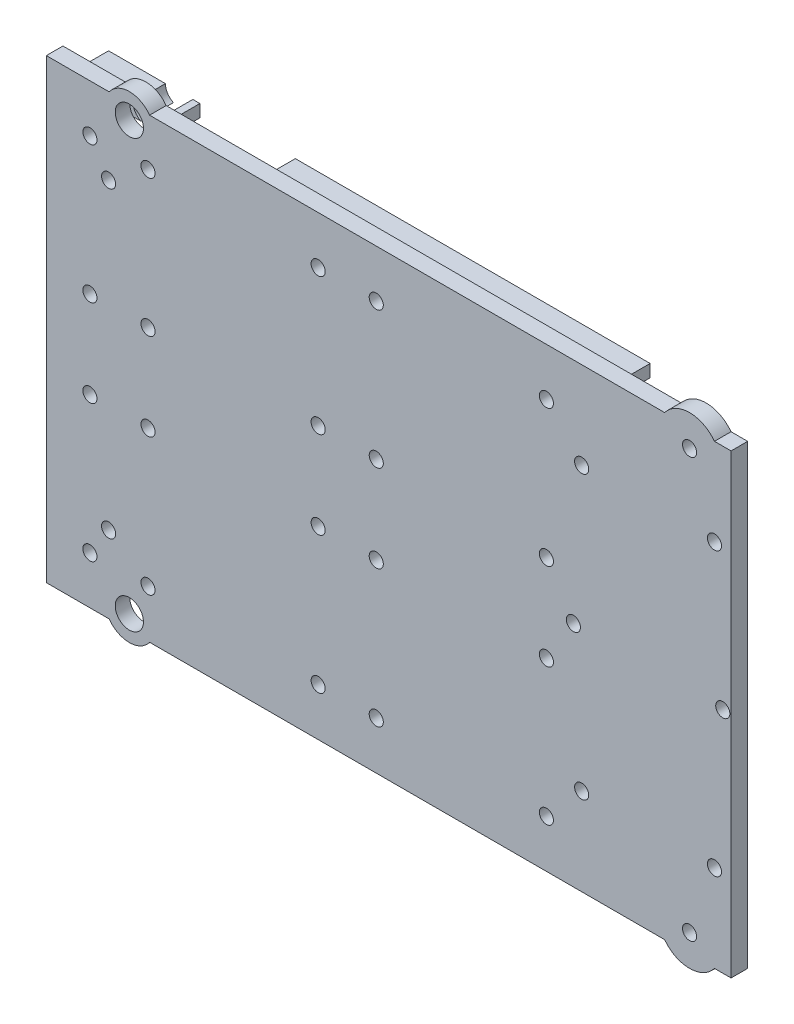
SolidWorks part; units mm, degrees
other "Platform Segment 3"
ref_plane "Front Plane" through (0, 0, 0) normal (0, 0, 1) x (1, 0, 0)
ref_plane "Top Plane" through (0, 0, 0) normal (0, 1, 0) x (1, 0, 0)
ref_plane "Right Plane" through (0, 0, 0) normal (1, 0, 0) x (0, 0, -1)
sketch3d "Main Profile Sketch datum points"
  point P0 (0, 0, 48.5)
  point P1 (10, 0, 48.5)
  point P2 (0, 10, 48.5)
ref_plane "Main Profile Sketch plane" through (0, 0, 48.5) normal (0, 0, 1) x (1, 0, 0)
sketch "Main Profile Sketch" plane through (0, 0, 48.5) normal (0, 0, 1) x (1, 0, 0)
  line L0 (55, -55) -> (70.1266, -55)
  line L1 (55, 55) -> (55, -55)
  line L2 (55, 55) -> (70.1266, 55)
  line L3 (79.8734, 55) -> (204, 55)
  line L4 (216, 55) -> (220, 55)
  line L5 (220, 55) -> (220, -55)
  line L6 (216, -55) -> (220, -55)
  line L7 (79.8734, -55) -> (204, -55)
  arc A0 (70.1266, -55) -> (79.8734, -55) centre (75, -51.5) ccw
  arc A1 (79.8734, 55) -> (70.1266, 55) centre (75, 51.5) ccw
  arc A2 (216, 55) -> (204, 55) centre (210, 50.5) ccw
  arc A3 (204, -55) -> (216, -55) centre (210, -50.5) ccw
  circle A4 centre (75, -51.5) radius 3.4
  circle A5 centre (65.5, -43.5) radius 1.7
  circle A6 centre (70, -36.5) radius 1.7
  circle A7 centre (79.5, -43.5) radius 1.7
  circle A8 centre (120.5, -43.5) radius 1.7
  circle A9 centre (134.5, -43.5) radius 1.7
  circle A10 centre (65.5, -10.5) radius 1.7
  circle A11 centre (79.5, -10.5) radius 1.7
  circle A12 centre (120.5, -10.5) radius 1.7
  circle A13 centre (134.5, -10.5) radius 1.7
  circle A14 centre (175.5, -43.5) radius 1.7
  circle A15 centre (210, -50.5) radius 1.7
  circle A16 centre (184, -34) radius 1.7
  circle A17 centre (216, -34) radius 1.7
  circle A18 centre (175.5, -10.5) radius 1.7
  circle A19 centre (65.5, 10.5) radius 1.7
  circle A20 centre (79.5, 10.5) radius 1.7
  circle A21 centre (120.5, 10.5) radius 1.7
  circle A22 centre (134.5, 10.5) radius 1.7
  circle A23 centre (70, 36.5) radius 1.7
  circle A24 centre (65.5, 43.5) radius 1.7
  circle A25 centre (75, 51.5) radius 3.4
  circle A26 centre (79.5, 43.5) radius 1.7
  circle A27 centre (120.5, 43.5) radius 1.7
  circle A28 centre (134.5, 43.5) radius 1.7
  circle A29 centre (175.5, 10.5) radius 1.7
  circle A30 centre (182, 0) radius 1.7
  circle A31 centre (218, 0) radius 1.7
  circle A32 centre (175.5, 43.5) radius 1.7
  circle A33 centre (184, 34) radius 1.7
  circle A34 centre (216, 34) radius 1.7
  circle A35 centre (210, 50.5) radius 1.7
extrude "Main Extrusion" add sketch "Main Profile Sketch" against normal blind 3.5 separate body
sketch3d "Detail Profile 2 Sketch datum points"
  point P0 (0, 0, 45)
  point P1 (10, 0, 45)
  point P2 (0, 10, 45)
ref_plane "Detail Profile 2 Sketch plane" through (0, 0, 45) normal (0, 0, 1) x (1, 0, 0)
sketch "Detail Profile 2 Sketch" plane through (0, 0, 45) normal (0, 0, 1) x (1, 0, 0)
  line L0 (55, -55) -> (70.1266, -55)
  line L1 (55, 55) -> (55, -55)
  line L2 (55, 55) -> (70.1266, 55)
  line L3 (79.8734, 55) -> (204, 55)
  line L4 (216, 55) -> (220, 55)
  line L5 (220, 55) -> (220, -55)
  line L6 (216, -55) -> (220, -55)
  line L7 (79.8734, -55) -> (204, -55)
  arc A0 (70.1266, -55) -> (79.8734, -55) centre (75, -51.5) ccw
  arc A1 (79.8734, 55) -> (70.1266, 55) centre (75, 51.5) ccw
  arc A2 (216, 55) -> (204, 55) centre (210, 50.5) ccw
  arc A3 (204, -55) -> (216, -55) centre (210, -50.5) ccw
  circle A4 centre (75, -51.5) radius 5.3
  circle A5 centre (65.5, -43.5) radius 1.7
  circle A6 centre (70, -36.5) radius 1.7
  circle A7 centre (79.5, -43.5) radius 1.7
  circle A8 centre (120.5, -43.5) radius 1.7
  circle A9 centre (134.5, -43.5) radius 1.7
  circle A10 centre (65.5, -10.5) radius 1.7
  circle A11 centre (79.5, -10.5) radius 1.7
  circle A12 centre (120.5, -10.5) radius 1.7
  circle A13 centre (134.5, -10.5) radius 1.7
  circle A14 centre (175.5, -43.5) radius 1.7
  circle A15 centre (210, -50.5) radius 1.7
  circle A16 centre (184, -34) radius 1.7
  circle A17 centre (216, -34) radius 1.7
  circle A18 centre (175.5, -10.5) radius 1.7
  circle A19 centre (65.5, 10.5) radius 1.7
  circle A20 centre (79.5, 10.5) radius 1.7
  circle A21 centre (120.5, 10.5) radius 1.7
  circle A22 centre (134.5, 10.5) radius 1.7
  circle A23 centre (70, 36.5) radius 1.7
  circle A24 centre (65.5, 43.5) radius 1.7
  circle A25 centre (75, 51.5) radius 5.3
  circle A26 centre (79.5, 43.5) radius 1.7
  circle A27 centre (120.5, 43.5) radius 1.7
  circle A28 centre (134.5, 43.5) radius 1.7
  circle A29 centre (175.5, 10.5) radius 1.7
  circle A30 centre (182, 0) radius 1.7
  circle A31 centre (218, 0) radius 1.7
  circle A32 centre (175.5, 43.5) radius 1.7
  circle A33 centre (184, 34) radius 1.7
  circle A34 centre (216, 34) radius 1.7
  circle A35 centre (210, 50.5) radius 1.7
extrude "Detail Extrusion 2" add sketch "Detail Profile 2 Sketch" against normal blind 0.5
sketch3d "Detail Profile 3 Sketch datum points"
  point P0 (0, 0, 44.5)
  point P1 (10, 0, 44.5)
  point P2 (0, 10, 44.5)
ref_plane "Detail Profile 3 Sketch plane" through (0, 0, 44.5) normal (0, 0, 1) x (1, 0, 0)
sketch "Detail Profile 3 Sketch" plane through (0, 0, 44.5) normal (0, 0, 1) x (1, 0, 0)
  line L0 (58, -48.5) -> (70.6308, -48.5)
  line L1 (58, -51.5) -> (69.7, -51.5)
  line L2 (58, -48.5) -> (58, -51.5)
  line L3 (79.3692, -48.5) -> (80, -48.5)
  line L4 (80, -48.5) -> (80, -49.7422)
  line L5 (103, -48.5) -> (103, -51.5)
  line L6 (103, -48.5) -> (188.5, -48.5)
  line L7 (188.5, -48.5) -> (188.5, -51.5)
  line L8 (103, -51.5) -> (188.5, -51.5)
  line L9 (58, 51.5) -> (58, 48.5)
  line L10 (58, 51.5) -> (69.7, 51.5)
  line L11 (58, 48.5) -> (70.6308, 48.5)
  line L12 (80, 49.7422) -> (80, 48.5)
  line L13 (79.3692, 48.5) -> (80, 48.5)
  line L14 (103, 51.5) -> (188.5, 51.5)
  line L15 (188.5, 51.5) -> (188.5, 48.5)
  line L16 (103, 48.5) -> (188.5, 48.5)
  line L17 (103, 51.5) -> (103, 48.5)
  arc A0 (70.6308, -48.5) -> (69.7, -51.5) centre (75, -51.5) ccw
  arc A1 (80, -49.7422) -> (79.3692, -48.5) centre (75, -51.5) ccw
  arc A2 (69.7, 51.5) -> (70.6308, 48.5) centre (75, 51.5) ccw
  arc A3 (79.3692, 48.5) -> (80, 49.7422) centre (75, 51.5) ccw
extrude "Detail Extrusion 3" add sketch "Detail Profile 3 Sketch" against normal blind 0.2
sketch3d "Detail Profile 4 Sketch datum points"
  point P0 (0, 0, 44.3)
  point P1 (10, 0, 44.3)
  point P2 (0, 10, 44.3)
ref_plane "Detail Profile 4 Sketch plane" through (0, 0, 44.3) normal (0, 0, 1) x (1, 0, 0)
sketch "Detail Profile 4 Sketch" plane through (0, 0, 44.3) normal (0, 0, 1) x (1, 0, 0)
  line L0 (58, -48.5) -> (73.6252, -48.5)
  line L1 (58, -51.5) -> (71.7, -51.5)
  line L2 (58, -48.5) -> (58, -51.5)
  line L3 (80, -48.5) -> (80, -51.5)
  line L4 (78.3, -51.5) -> (80, -51.5)
  line L5 (76.3748, -48.5) -> (80, -48.5)
  line L6 (103, -48.5) -> (103, -51.5)
  line L7 (103, -48.5) -> (188.5, -48.5)
  line L8 (188.5, -48.5) -> (188.5, -51.5)
  line L9 (103, -51.5) -> (188.5, -51.5)
  line L10 (58, 51.5) -> (58, 48.5)
  line L11 (58, 51.5) -> (71.7, 51.5)
  line L12 (58, 48.5) -> (73.6252, 48.5)
  line L13 (78.3, 51.5) -> (80, 51.5)
  line L14 (80, 51.5) -> (80, 48.5)
  line L15 (76.3748, 48.5) -> (80, 48.5)
  line L16 (103, 51.5) -> (188.5, 51.5)
  line L17 (188.5, 51.5) -> (188.5, 48.5)
  line L18 (103, 48.5) -> (188.5, 48.5)
  line L19 (103, 51.5) -> (103, 48.5)
  arc A0 (73.6252, -48.5) -> (71.7, -51.5) centre (75, -51.5) ccw
  arc A1 (78.3, -51.5) -> (76.3748, -48.5) centre (75, -51.5) ccw
  arc A2 (71.7, 51.5) -> (73.6252, 48.5) centre (75, 51.5) ccw
  arc A3 (76.3748, 48.5) -> (78.3, 51.5) centre (75, 51.5) ccw
extrude "Detail Extrusion 4" add sketch "Detail Profile 4 Sketch" against normal blind 7.8
